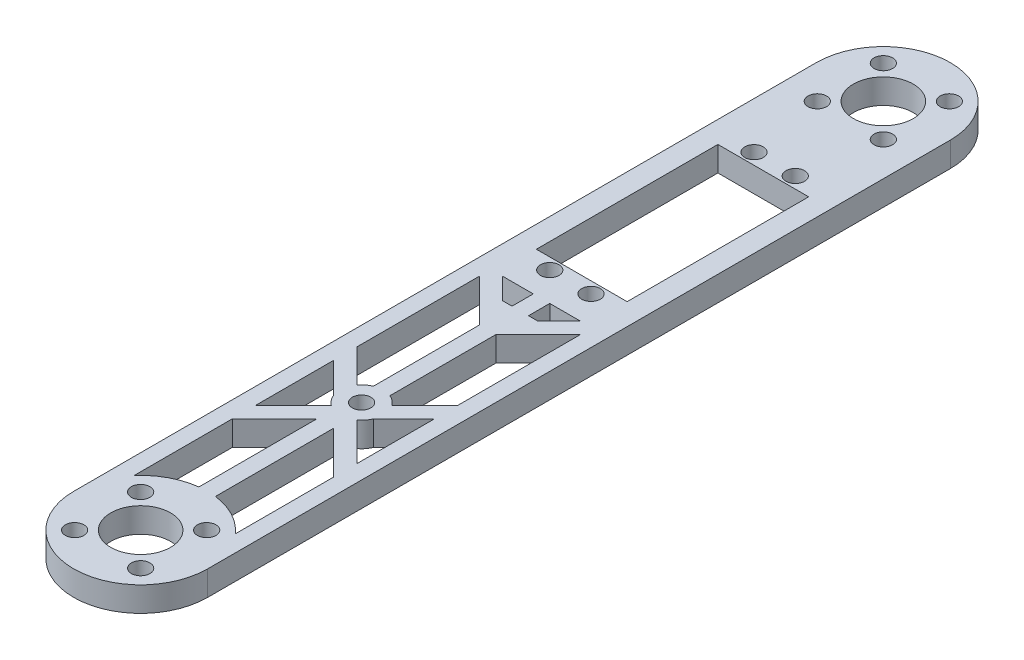
SolidWorks part; units mm, degrees
ref_plane "Front Plane" through (0, 0, 0) normal (0, 0, 1) x (1, 0, 0)
ref_plane "Top Plane" through (0, 0, 0) normal (0, 1, 0) x (1, 0, 0)
ref_plane "Right Plane" through (0, 0, 0) normal (1, 0, 0) x (0, 0, -1)
sketch "Sketch2" plane through (0, 0, 0) normal (0, 1, 0) x (1, 0, 0)
  line L0 (0, 0) -> (-127946.3425, 0) construction
  line L1 (0, 0) -> (0, 127946.3425) construction
  line L2 (-16.25, 90) -> (-16.25, -90)
  line L3 (16.25, 90) -> (16.25, -90)
  line L4 (-20.25, 90) -> (-20.25, -90) construction
  line L5 (8, 82) -> (-8, 82) construction
  line L6 (8, 82) -> (8, 98) construction
  line L7 (8, 98) -> (-8, 98) construction
  line L8 (-8, 82) -> (-8, 98) construction
  line L9 (0, 98) -> (0, 82) construction
  line L10 (8, 90) -> (-8, 90) construction
  line L11 (-8, -82) -> (8, -82) construction
  line L12 (-8, -82) -> (-8, -98) construction
  line L13 (-8, -98) -> (8, -98) construction
  line L14 (8, -82) -> (8, -98) construction
  line L15 (0, -98) -> (0, -82) construction
  line L16 (-8, -90) -> (8, -90) construction
  line L17 (20.25, 90) -> (20.25, -90) construction
  line L18 (-12.25, 90) -> (-12.25, -90) construction
  line L19 (12.25, 90) -> (12.25, -90) construction
  line L20 (-28.9926, 9.1528) -> (49971.0074, 9.1528) construction
  line L21 (-11, 60.9028) -> (11, 60.9028)
  line L22 (-11, 60.9028) -> (-11, 16.9028)
  line L23 (-11, 16.9028) -> (11, 16.9028)
  line L24 (11, 60.9028) -> (11, 16.9028)
  line L25 (0, 16.9028) -> (0, 60.9028) construction
  line L26 (-11, 38.9028) -> (11, 38.9028) construction
  line L27 (-5, 63.6528) -> (5, 63.6528) construction
  line L28 (-5, 63.6528) -> (-5, 14.1528) construction
  line L29 (-5, 14.1528) -> (5, 14.1528) construction
  line L30 (5, 63.6528) -> (5, 14.1528) construction
  line L31 (0, 14.1528) -> (0, 63.6528) construction
  line L32 (-5, 38.9028) -> (5, 38.9028) construction
  line L33 (0, 73.75) -> (50000, 73.75) construction
  line L34 (-42.0204, -73.75) -> (49957.9796, -73.75) construction
  line L35 (20.7937, 17.6965) -> (-35334.5454, -35337.6426) construction
  line L36 (-202.4933, 164.0408) -> (35152.6914, -35191.1439) construction
  line L37 (-152.696, 149.5988) -> (35202.4887, -35205.5859) construction
  line L38 (-24.1771, -62.6297) -> (35331.162, 35292.7094) construction
  line L39 (-198.3624, 124.5545) -> (35156.9767, -35230.7846) construction
  line L40 (-34.0458, -107.8537) -> (35321.2932, 35247.4854) construction
  line L41 (-199.7766, 123.1402) -> (35155.5625, -35232.1988) construction
  line L42 (-203.9075, 162.6266) -> (35151.2772, -35192.5581) construction
  line L43 (-154.1102, 148.1846) -> (35201.0745, -35207.0001) construction
  line L44 (19.3795, 19.1107) -> (-35335.9596, -35336.2284) construction
  line L45 (-22.7629, -64.0439) -> (35332.5762, 35291.2952) construction
  line L46 (-32.6316, -109.2679) -> (35322.7075, 35246.0711) construction
  line L47 (-28.9926, 7.1528) -> (49971.0074, 7.1528) construction
  line L48 (-42.0204, -75.75) -> (49957.9796, -75.75) construction
  line L49 (-196.9481, 125.9687) -> (35158.3909, -35229.3704) construction
  line L50 (-201.0791, 165.455) -> (35154.1056, -35189.7297) construction
  line L51 (-151.2818, 151.013) -> (35203.9029, -35204.1717) construction
  line L52 (22.2079, 16.2823) -> (-35333.1312, -35339.0568) construction
  line L53 (-25.5913, -61.2154) -> (35329.7477, 35294.1236) construction
  line L54 (-35.46, -106.4395) -> (35319.879, 35248.8996) construction
  line L55 (-28.9926, 11.1528) -> (49971.0074, 11.1528) construction
  line L56 (-42.0204, -71.75) -> (49957.9796, -71.75) construction
  line L57 (2, 0) -> (2, 127946.3425) construction
  line L58 (-2, 0) -> (-2, 127946.3425) construction
  line L64 (19.0801, 49.5321) -> (12.6868, -90.5789) construction
  line L65 (-12.6868, -90.5789) -> (-19.0801, 49.5321) construction
  circle A0 centre (0, 90) radius 7.25
  circle A1 centre (0, -90) radius 7.25
  arc A2 (16.25, 90) -> (-16.25, 90) centre (0, 90) ccw
  arc A3 (-16.25, -90) -> (16.25, -90) centre (0, -90) ccw
  circle A4 centre (8, 98) radius 2.25
  circle A5 centre (-8, 98) radius 2.25
  circle A6 centre (-8, 82) radius 2.25
  circle A7 centre (8, 82) radius 2.25
  circle A8 centre (8, -98) radius 2.25
  circle A9 centre (8, -82) radius 2.25
  circle A10 centre (-8, -82) radius 2.25
  circle A11 centre (-8, -98) radius 2.25
  arc A12 (-20.25, -90) -> (20.25, -90) centre (0, -90) ccw construction
  arc A13 (20.25, 90) -> (-20.25, 90) centre (0, 90) ccw construction
  arc A14 (-12.25, -90) -> (12.25, -90) centre (0, -90) ccw construction
  arc A15 (12.25, 90) -> (-12.25, 90) centre (0, 90) ccw construction
  arc A16 (-16.25, 90) -> (16.25, 90) centre (0, 90) ccw construction
  circle A17 centre (-5, 63.6528) radius 2.25
  circle A18 centre (5, 63.6528) radius 2.25
  circle A19 centre (-5, 14.1528) radius 2.25
  circle A20 centre (5, 14.1528) radius 2.25
  circle A21 centre (0, 50.4028) radius 7 construction
  arc A22 (-16.25, -90) -> (16.25, -90) centre (0, -90) cw construction
  circle A23 centre (0, 50.4028) radius 19.1 construction
  circle A24 centre (0, -90) radius 12.7 construction
  arc A25 (-19.0801, 49.5321) -> (19.0801, 49.5321) centre (0, 50.4028) cw construction
  arc A26 (-12.6868, -90.5789) -> (12.6868, -90.5789) centre (0, -90) ccw construction
  circle A27 centre (0, -36.453) radius 2.25
  point P16 (0, -90)
  point P29 (0, 38.9028)
  point P42 (0, 38.9028)
  point P59 (0, 73.75)
  point P63 (-12.25, 9.1528)
  point P64 (12.25, 9.1528)
  dimension "D3" = 14.5
  dimension "D4" = 32.5
  dimension "D7" = 4.5
  dimension "D12" = 4.5
  dimension "D14" = 14
  dimension "D25" = 25.4
  dimension "D26" = 38.2
  dimension "4.5" = 4.5
  dimension "D6" = 16
  dimension "D1" = 90
  dimension "D8" = 22
  dimension "D9" = 44
  dimension "D10" = 10
  dimension "D11" = 49.5
  dimension "D13" = 13.25
  dimension "D15" = 5
  dimension "D16" = 45
  dimension "D17" = 25
  dimension "D18" = 25
  dimension "D19" = 25
  dimension "D20" = 25
  dimension "D28" = 53.547
  dimension "D2" = 4
  dimension "D5" = 4
  dimension "D21" = 2
  dimension "D22" = 2
  dimension "D23" = 2
  dimension "D24" = 2
extrude "Boss-Extrude1" add sketch "Sketch2" along normal blind 6
sketch "Sketch3" plane through (0, 6, 0) normal (0, 1, 0) x (1, 0, 0)
  line L0 (0, 0) -> (50000, 0) construction
  line L1 (0, -1071.2483) -> (0, 50000) construction
  line L2 (2.9662, 90) -> (50002.9662, 90) construction
  line L3 (2.6055, -90) -> (50002.6055, -90) construction
  line L4 (16.25, 44.2284) -> (16.25, 50044.2284) construction
  line L5 (0, -75.75) -> (50000, -75.75) construction
  line L6 (-16.25, 67.8715) -> (-16.25, 50067.8715) construction
  line L7 (2.6055, -92) -> (50002.6055, -92) construction
  line L8 (0, -73.75) -> (50000, -73.75) construction
  line L9 (0, 73.75) -> (50000, 73.75) construction
  line L11 (-16.25, 90) -> (-16.25, -90) construction
  line L12 (2, -1071.2483) -> (2, -35.6241) construction
  line L13 (0, -2) -> (50000, -2) construction
  line L14 (0, -71.75) -> (50000, -71.75) construction
  line L15 (2.6055, -88) -> (50002.6055, -88) construction
  line L16 (-2, -1071.2483) -> (-2, -35.6241) construction
  line L17 (0, 2) -> (50000, 2) construction
  line L18 (2.9662, 88) -> (50002.9662, 88) construction
  line L19 (0, 71.75) -> (50000, 71.75) construction
  line L20 (2.9662, 92) -> (50002.9662, 92) construction
  line L21 (0, 75.75) -> (50000, 75.75) construction
  line L22 (-12.25, 67.8715) -> (-12.25, 50067.8715) construction
  line L23 (20.25, 44.2284) -> (20.25, 50044.2284) construction
  line L24 (-20.25, 67.8715) -> (-20.25, 50067.8715) construction
  line L25 (12.25, 44.2284) -> (12.25, 50044.2284) construction
  line L26 (-29.0229, 9.1528) -> (49970.9771, 9.1528) construction
  line L27 (-29.0229, 7.1528) -> (49970.9771, 7.1528) construction
  line L28 (-29.0229, 11.1528) -> (49970.9771, 11.1528) construction
  line L29 (-14.7986, 9.7014) -> (35340.5405, -35345.6377) construction
  line L30 (14.7986, 9.7014) -> (-35340.5405, -35345.6377) construction
  line L31 (-39.9106, -0.5419) -> (35315.4284, -35355.881) construction
  line L32 (-55.3654, -20.4425) -> (35299.9737, -35375.7816) construction
  line L33 (38.3787, 68.6368) -> (-35316.9604, -35286.7023) construction
  line L34 (132.1398, 91.6873) -> (-35223.1992, -35263.6518) construction
  line L35 (66.2569, -35.9988) -> (-35289.0821, 35319.3402) construction
  line L36 (-100.6946, -176.5025) -> (35254.6445, 35178.8366) construction
  line L37 (36.9644, 70.051) -> (-35318.3746, -35285.2881) construction
  line L38 (13.3844, 11.1156) -> (-35341.9547, -35344.2235) construction
  line L39 (130.7256, 93.1015) -> (4.2514, -33.3727) construction
  line L40 (-99.2804, -177.9167) -> (35256.0587, 35177.4224) construction
  line L41 (67.6712, -34.5846) -> (-35287.6679, 35320.7544) construction
  line L42 (-16.2128, 8.2872) -> (35339.1262, -35347.0519) construction
  line L43 (-41.3248, -1.9561) -> (-4.872, -38.4089) construction
  line L44 (-56.7796, -21.8568) -> (35298.5595, -35377.1958) construction
  line L45 (39.7929, 67.2226) -> (-35315.5462, -35288.1165) construction
  line L46 (16.2128, 8.2872) -> (-35339.1262, -35347.0519) construction
  line L47 (133.554, 90.2731) -> (4.872, -38.4089) construction
  line L48 (-102.1088, -175.0883) -> (35253.2303, 35180.2508) construction
  line L49 (64.8427, -37.413) -> (-35290.4963, 35317.926) construction
  line L50 (-13.3844, 11.1156) -> (35341.9547, -35344.2235) construction
  line L51 (-38.4964, 0.8723) -> (-4.2514, -33.3727) construction
  line L52 (-53.9511, -19.0283) -> (35301.3879, -35374.3674) construction
  line L53 (-2, -45.281) -> (-12.25, -55.531)
  line L54 (-12.25, -55.531) -> (-12.25, -79.3229)
  line L56 (-2, -45.281) -> (-2, -73.8735)
  line L57 (-12.25, 4.3244) -> (-2, -5.9256)
  line L58 (-2, -5.9256) -> (-2, -31.5989)
  line L59 (-4.2514, -33.3727) -> (-12.25, -25.3741)
  line L60 (-12.25, -25.3741) -> (-12.25, 4.3244)
  line L61 (-12.25, -31.031) -> (-12.25, -49.8741)
  line L62 (-12.25, -49.8741) -> (-3.0803, -40.7044)
  line L63 (-4.872, -38.4089) -> (-12.25, -31.031)
  line L64 (-9.4216, 7.1528) -> (-2, 7.1528)
  line L65 (-2, 7.1528) -> (-2, 2)
  line L66 (-2, 2) -> (-4.2688, 2)
  line L67 (-4.2688, 2) -> (-9.4216, 7.1528)
  line L68 (2, -45.281) -> (12.25, -55.531)
  line L69 (12.25, -55.531) -> (12.25, -79.3229)
  line L70 (2, -45.281) -> (2, -73.8735)
  line L71 (12.25, -49.8741) -> (3.0803, -40.7044)
  line L72 (12.25, -31.031) -> (12.25, -49.8741)
  line L73 (4.872, -38.4089) -> (12.25, -31.031)
  line L74 (2, 2) -> (4.2688, 2)
  line L75 (2, 7.1528) -> (2, 2)
  line L76 (9.4216, 7.1528) -> (2, 7.1528)
  line L77 (4.2688, 2) -> (9.4216, 7.1528)
  line L78 (4.2514, -33.3727) -> (12.25, -25.3741)
  line L79 (2, -5.9256) -> (2, -31.5989)
  line L80 (12.25, 4.3244) -> (2, -5.9256)
  line L81 (12.25, -25.3741) -> (12.25, 4.3244)
  line L82 (-2.8284, -40.4526) -> (35314.0142, -35357.2952) construction
  line L84 (-3.0803, -40.7044) -> (-35224.6135, -35262.2376) construction
  line L86 (-2, -35.6241) -> (2.8284, -40.4526) construction
  line L88 (-2, -31.5989) -> (-2, 50000) construction
  line L90 (2, -31.5989) -> (2, 50000) construction
  line L92 (2, -35.6241) -> (-2.8284, -40.4526) construction
  line L93 (2.8284, -40.4526) -> (-35221.785, -35265.066) construction
  line L95 (3.0803, -40.7044) -> (35316.8426, -35354.4668) construction
  circle A0 centre (0, 90) radius 16.25 construction
  circle A1 centre (0, -90) radius 16.25 construction
  arc A2 (16.25, 90) -> (-16.25, 90) centre (0, 90) ccw construction
  arc A4 (-12.25, -79.3229) -> (-2, -73.8735) centre (0, -90) cw
  arc A5 (12.25, -79.3229) -> (2, -73.8735) centre (0, -90) ccw
  arc A8 (4.2514, -33.3727) -> (2, -31.5989) centre (0, -36.453) ccw
  circle A9 centre (0, -36.453) radius 5.25
  arc A10 (-4.872, -38.4089) -> (-3.0803, -40.7044) centre (0, -36.453) ccw
  arc A11 (-2, -41.3071) -> (-1.9559, -41.325) centre (0, -36.453) ccw
  arc A12 (-2, -31.5989) -> (-4.2514, -33.3727) centre (0, -36.453) ccw
  arc A13 (3.0803, -40.7044) -> (4.872, -38.4089) centre (0, -36.453) ccw
  point P70 (-12.25, 7.1528)
  point P71 (12.25, 7.1528)
  point P160 (-204.4977, 19.6393)
  point P163 (-204.2899, 6.9621)
  dimension "D19" = 3
extrude "Cut-Extrude1" cut sketch "Sketch3" against normal blind 26 contours A12 L58 L57 L60 L59 | A8 L78 L81 L80 L79 | A10 L63 L61 L62 | A13 L71 L72 L73 | L54 A4 L56 L53 | A5 L69 L68 L70 | L67 L66 L65 L64 | L74 L77 L76 L75
equation "\"pocketing\"= 2mm'hole"
equation "\"D5@Sketch2\"=\"pocketing\"*2"
equation "\"D2@Sketch2\"=\"pocketing\"*2"
equation "\"D24@Sketch2\"=\"pocketing\""
equation "\"D23@Sketch2\"=\"pocketing\""
equation "\"D22@Sketch2\"=\"pocketing\""
equation "\"D21@Sketch2\"=\"pocketing\""
